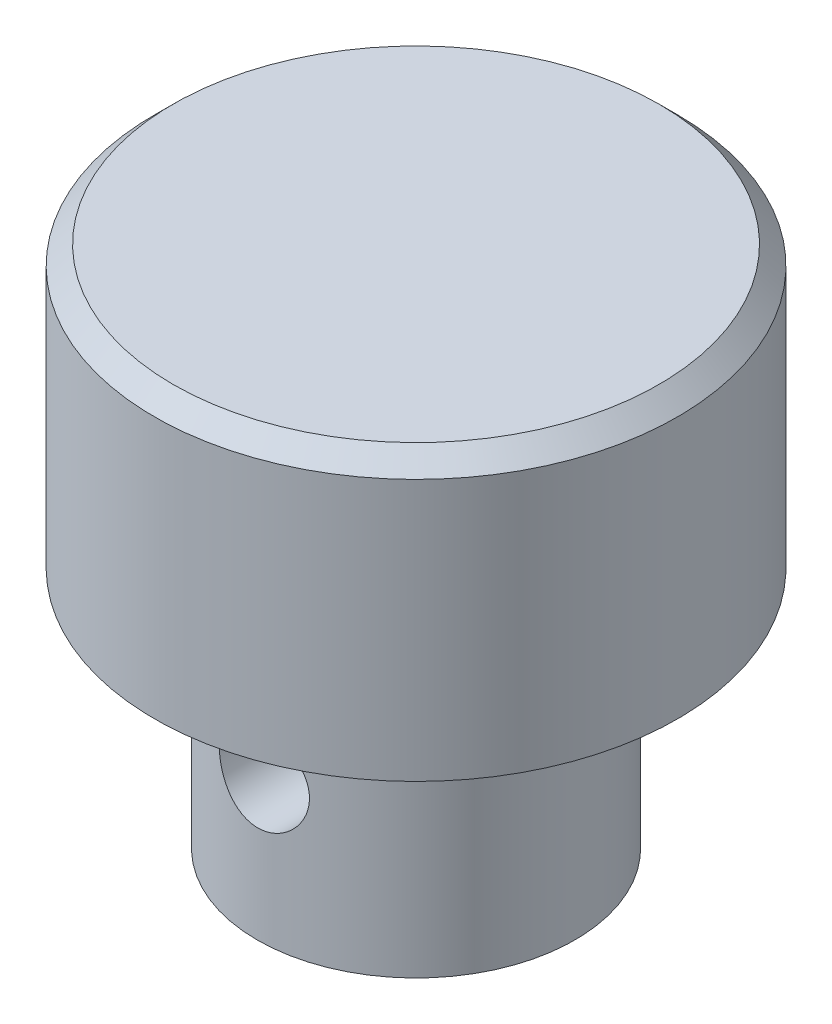
SolidWorks part; units mm, degrees
material "Ottone"
ref_plane "Piano frontale" through (0, 0, 0) normal (0, 0, 1) x (1, 0, 0)
ref_plane "Piano superiore" through (0, 0, 0) normal (0, 1, 0) x (1, 0, 0)
ref_plane "Piano destro" through (0, 0, 0) normal (1, 0, 0) x (0, 0, -1)
sketch "Schizzo1" plane through (0, 0, 0) normal (0, 0, 1) x (1, 0, 0)
  line L0 (-7, 14) -> (-7, 6.5)
  line L1 (-7, 6.5) -> (-4.25, 6.5)
  line L2 (-4.25, 6.5) -> (-4.25, 0)
  line L3 (-4.25, 0) -> (0, 0)
  line L4 (0, 0) -> (0, 14)
  line L5 (0, 14) -> (-7, 14)
  line L6 (0, 0) -> (0, 21.5243) construction
  dimension "D1" = 14
  dimension "D2" = 7.5
  dimension "D3" = 14
  dimension "D4" = 8.5
revolve "Rivoluzione1" add sketch "Schizzo1" angle 360 about L6
chamfer "Smusso1" distance 0.5 angle 45 1 edges at (0, 14, -7)
sketch "Schizzo2" plane through (0, 0, 0) normal (0, -1, 0) x (-1, 0, 0)
  circle A0 centre (0, 0) radius 1.5
  dimension "D1" = 3
extrude "Taglio-Estrusione1" cut sketch "Schizzo2" against normal blind 10
hole_wizard "Foro per Vite M2-2" positions "Schizzo3D2" profile "Schizzo4" hole size "M2" standard "ISO"
sketch3d "Schizzo3D2"
  line L0 (0, 0, 0) -> (0, 14.2556, 0) construction
  point P0 (0.02, 3.8057, 4.25)
sketch "Schizzo4" plane through (0.02, 3.8057, 4.25) normal (0, 1, 0) x (1, 0, -0.0047)
  line L0 (0, 0) -> (0, 2.75)
  line L1 (0, 2.75) -> (1.2, 2.75)
  line L2 (1.2, 2.75) -> (1.2, 0)
  line L5 (1.2, 0) -> (0, 0)
  line L11 (0, -6.35) -> (0, 107.95) construction
  dimension "Thru Hole Dia." = 2.4
  dimension "Thru Hole Depth" = 2.75
